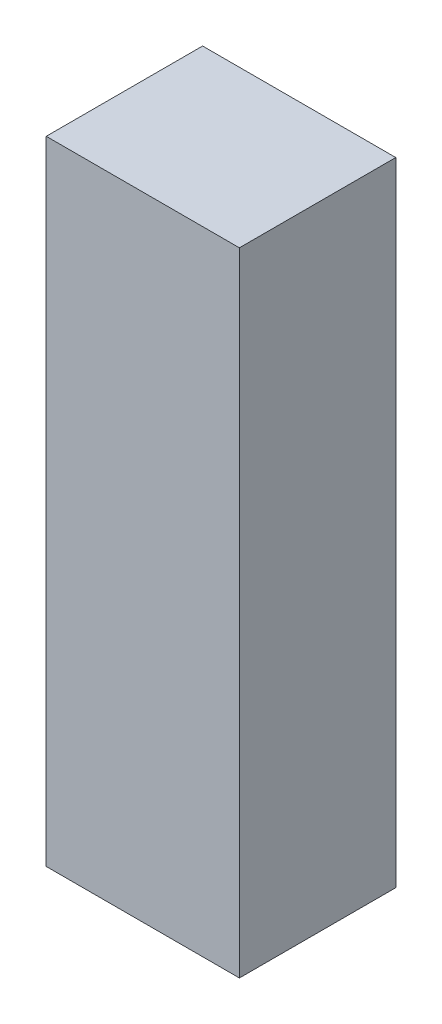
SolidWorks part; units mm, degrees
ref_plane "Front Plane" through (0, 0, 0) normal (0, 0, 1) x (1, 0, 0)
ref_plane "Top Plane" through (0, 0, 0) normal (0, 1, 0) x (1, 0, 0)
ref_plane "Right Plane" through (0, 0, 0) normal (1, 0, 0) x (0, 0, -1)
sketch "Sketch1" plane through (0, 0, 0) normal (0, 1, 0) x (1, 0, 0)
  line L1 (-59.7467, 24.5933) -> (24.2533, 24.5933)
  line L2 (-59.7467, 24.5933) -> (-59.7467, -43.4067)
  line L3 (-59.7467, -43.4067) -> (24.2533, -43.4067)
  line L4 (24.2533, 24.5933) -> (24.2533, -43.4067)
  line L5 (-59.7467, 24.5933) -> (24.2533, -43.4067) construction
  line L6 (-59.7467, -43.4067) -> (24.2533, 24.5933) construction
  point P4 (-17.7467, -9.4067)
  dimension "D1" = 68
  dimension "D2" = 84
extrude "Boss-Extrude1" add sketch "Sketch1" along normal blind 275
